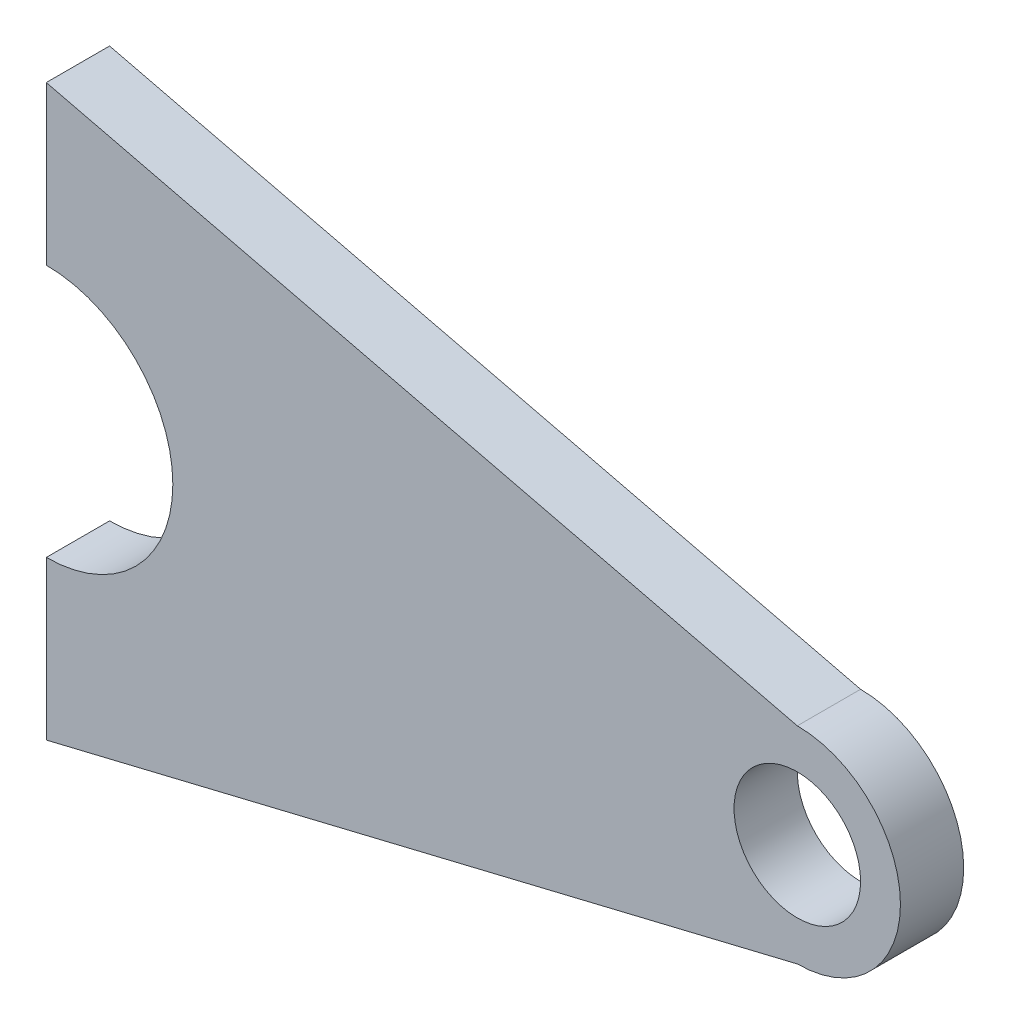
SolidWorks part; units mm, degrees
ref_plane "Front Plane" through (0, 0, 0) normal (0, 0, 1) x (1, 0, 0)
ref_plane "Top Plane" through (0, 0, 0) normal (0, 1, 0) x (1, 0, 0)
ref_plane "Right Plane" through (0, 0, 0) normal (1, 0, 0) x (0, 0, -1)
sketch "Sketch1" plane through (0, 0, 0) normal (0, 0, 1) x (1, 0, 0)
  line L0 (10.35, 0) -> (-62.675, 0) construction
  line L1 (-75.375, 28.575) -> (0, 10.35)
  line L2 (0, -10.35) -> (-75.375, -28.575)
  line L3 (-75.375, 28.575) -> (-75.375, 12.7)
  line L4 (-75.375, -12.7) -> (-75.375, -28.575)
  circle A0 centre (0, 0) radius 6.35
  arc A1 (0, -10.35) -> (0, 10.35) centre (0, 0) ccw
  arc A2 (-75.375, -12.7) -> (-75.375, 12.7) centre (-75.375, 0) ccw
  circle A6 centre (0, 0) radius 10.35 construction
  dimension "D1" = 12.7
  dimension "D4" = 25.4
  dimension "D3" = 85.725
  dimension "D5" = 57.15
  dimension "D2" = 4
extrude "Boss-Extrude1" add sketch "Sketch1" along normal blind 6.35
